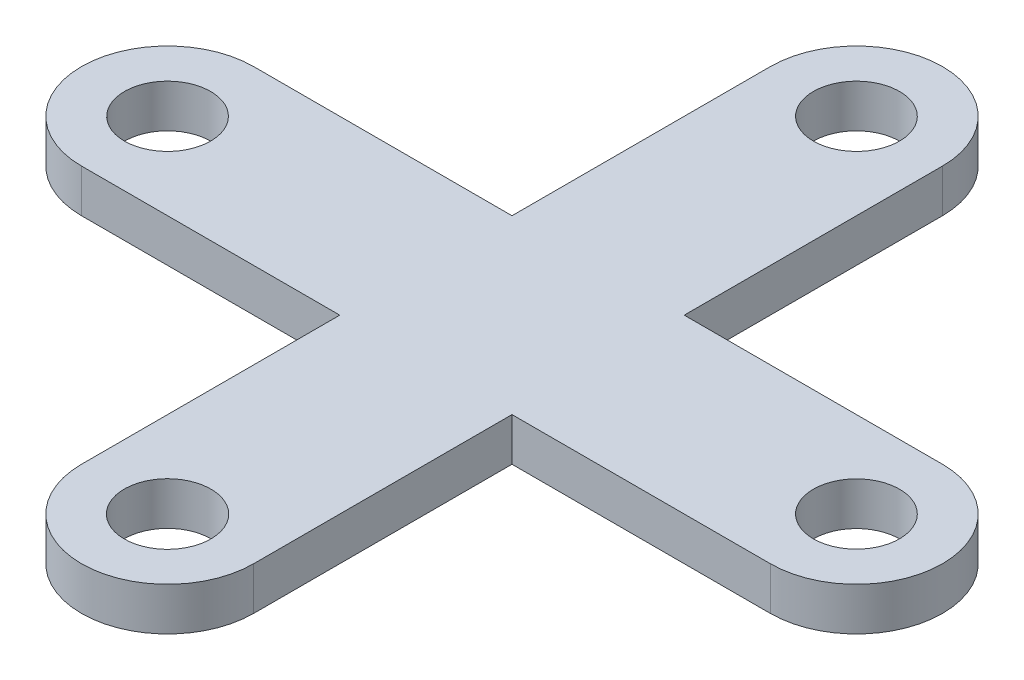
SolidWorks part; units mm, degrees
material "AISI 1020"
ref_plane "Front Plane" through (0, 0, 0) normal (0, 0, 1) x (1, 0, 0)
ref_plane "Top Plane" through (0, 0, 0) normal (0, 1, 0) x (1, 0, 0)
ref_plane "Right Plane" through (0, 0, 0) normal (1, 0, 0) x (0, 0, -1)
sketch "Sketch1" plane through (0, 0, 0) normal (0, 1, 0) x (1, 0, 0)
  line L0 (0, 74.1616) -> (0, -27.4384) construction
  line L1 (12.7, 74.1616) -> (12.7, -27.4384)
  line L2 (-12.7, 74.1616) -> (-12.7, -27.4384)
  line L3 (-50.8, 23.3616) -> (50.8, 23.3616) construction
  line L4 (-50.8, 36.0616) -> (50.8, 36.0616)
  line L5 (-50.8, 10.6616) -> (50.8, 10.6616)
  arc A0 (12.7, 74.1616) -> (-12.7, 74.1616) centre (0, 74.1616) ccw
  arc A1 (-12.7, -27.4384) -> (12.7, -27.4384) centre (0, -27.4384) ccw
  arc A2 (-50.8, 36.0616) -> (-50.8, 10.6616) centre (-50.8, 23.3616) ccw
  arc A3 (50.8, 10.6616) -> (50.8, 36.0616) centre (50.8, 23.3616) ccw
  point P3 (0, 23.3616)
  point P10 (0, 23.3616)
  dimension "D1" = 25.4
  dimension "D2" = 101.6
  dimension "D3" = 25.4
  dimension "D4" = 101.6
  dimension "D5" = 71.842
  dimension "D6" = 71.842
extrude "Boss-Extrude1" add sketch "Sketch1" along normal blind 6.35 contours L1 A0 L2 L4 | L5 A3 L4 L1 | L2 A1 L1 L5 | L4 A2 L5 L2 | L2 L5 L1 L4
sketch "Sketch2" plane through (0, 6.35, 0) normal (0, 1, 0) x (1, 0, 0)
  circle A0 centre (0, 74.1616) radius 6.35
  circle A1 centre (-50.8, 23.3616) radius 6.35
  circle A2 centre (0, -27.4384) radius 6.3821
  circle A3 centre (50.8, 23.3616) radius 6.35
  dimension "D1" = 12.7
  dimension "D2" = 12.7
  dimension "D3" = 12.7642
  dimension "D4" = 12.7
extrude "Cut-Extrude1" cut sketch "Sketch2" against normal through all
sketch "Sketch3" plane through (0, 0, 0) normal (0, 1, 0) x (1, 0, 0)
  line L1 (-12.7, 11.9616) -> (12.2603, 11.9616)
  line L2 (-12.7, 11.9616) -> (-12.7, 35.1917)
  line L3 (-12.7, 35.1917) -> (12.2603, 35.1917)
  line L4 (12.2603, 11.9616) -> (12.2603, 35.1917)
extrude "Cut-Extrude2" cut sketch "Sketch3" along normal blind 2.54 contours L1 L4 L3 L2
